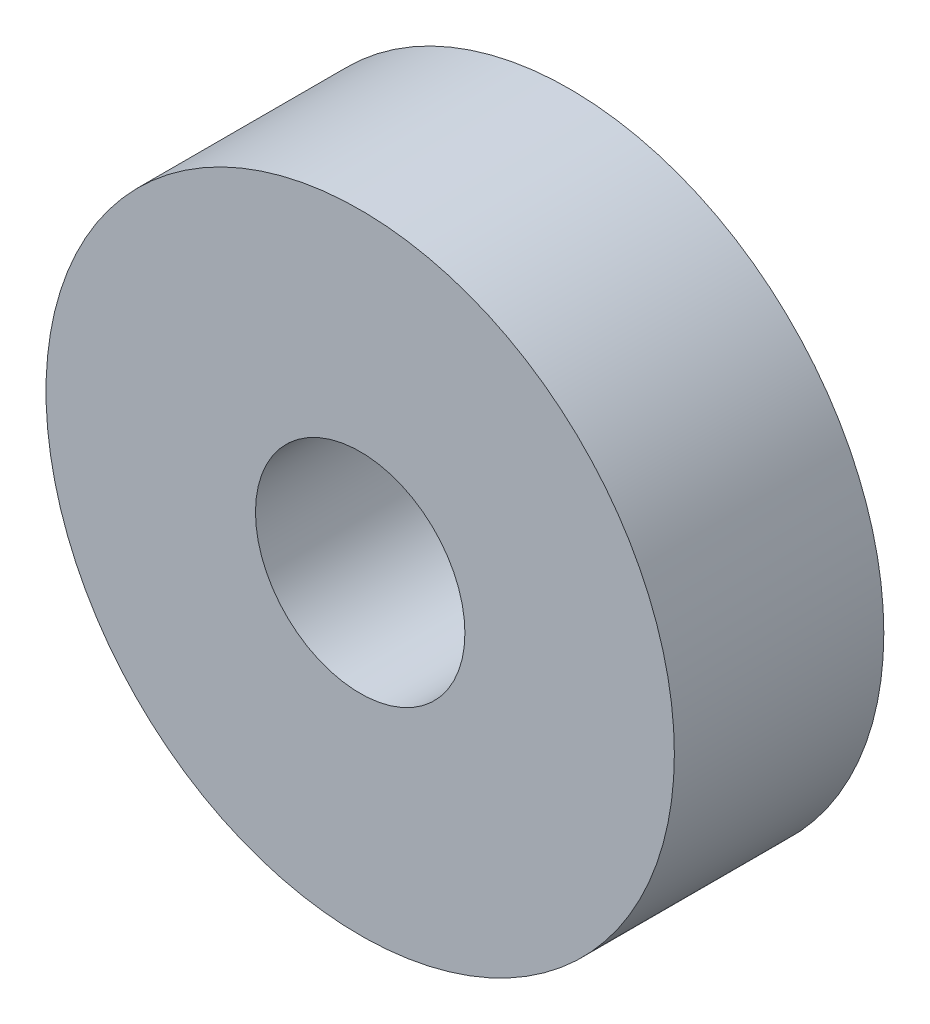
SolidWorks part; units mm, degrees
other "Bearing_3-1-1"
material "1.5714 (16NiCr4)"
ref_plane "Front" through (0, 0, 0) normal (0, 0, 1) x (1, 0, 0)
ref_plane "Top" through (0, 0, 0) normal (0, 1, 0) x (1, 0, 0)
ref_plane "Right" through (0, 0, 0) normal (1, 0, 0) x (0, 0, -1)
sketch "BearingSke" plane through (0, 0, 0) normal (0, 0, 1) x (1, 0, 0)
  circle A0 centre (0, 0) radius 1.5
  circle A1 centre (0, 0) radius 0.5
  dimension "D1" = 3
  dimension "D2" = 1
extrude "Bearing" add sketch "BearingSke" along normal blind 1
